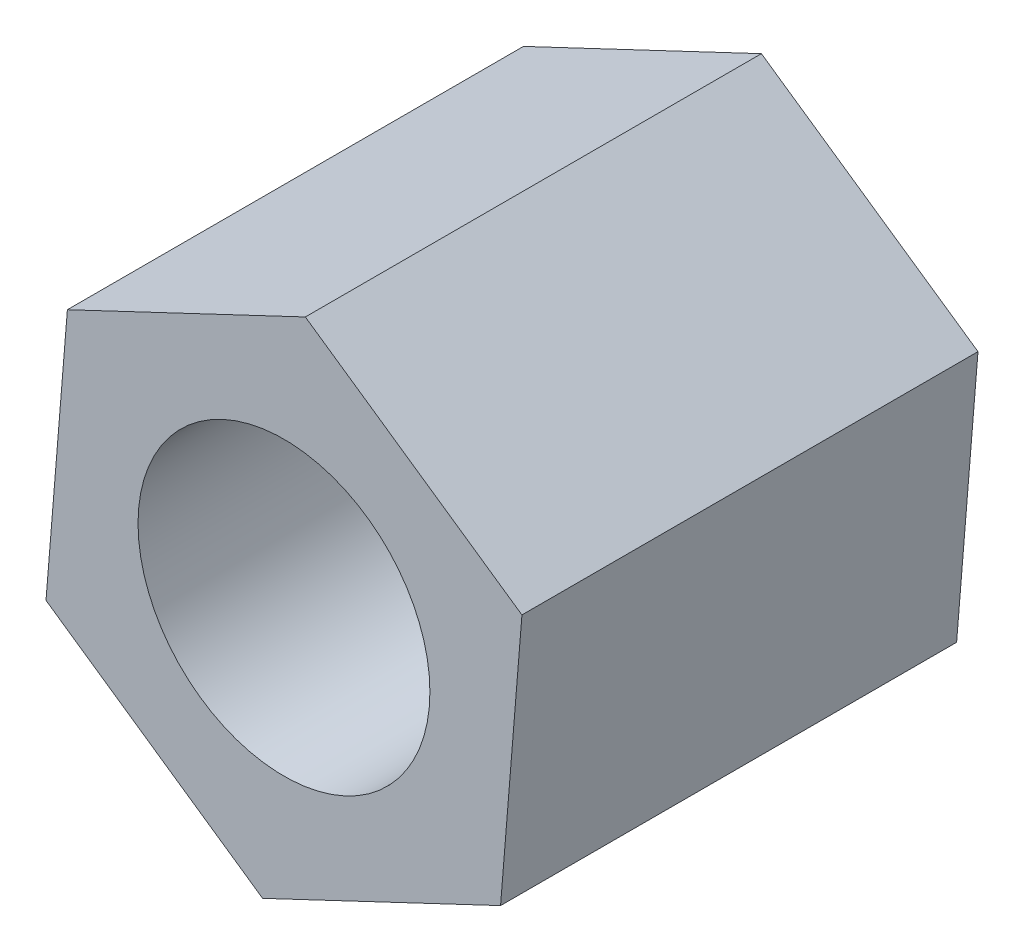
SolidWorks part; units mm, degrees
ref_plane "Front Plane" through (0, 0, 0) normal (0, 0, 1) x (1, 0, 0)
ref_plane "Top Plane" through (0, 0, 0) normal (0, 1, 0) x (1, 0, 0)
ref_plane "Right Plane" through (0, 0, 0) normal (1, 0, 0) x (0, 0, -1)
sketch "Sketch1" plane through (0, 0, 0) normal (0, 0, 1) x (1, 0, 0)
  line L1 (-2.3745, 1.6416) -> (-2.609, -1.2356)
  line L2 (-2.609, -1.2356) -> (-0.2344, -2.8772)
  line L3 (-0.2344, -2.8772) -> (2.3745, -1.6416)
  line L4 (2.3745, -1.6416) -> (2.609, 1.2356)
  line L5 (2.609, 1.2356) -> (0.2344, 2.8772)
  line L6 (0.2344, 2.8772) -> (-2.3745, 1.6416)
  circle A0 centre (0, 0) radius 2.5 construction
  dimension "D1" = 5
extrude "Boss-Extrude1" add sketch "Sketch1" along normal blind 5
sketch "Sketch2" plane through (0, 0, 5) normal (0, 0, 1) x (1, 0, 0)
  circle A0 centre (0, 0) radius 1.6
extrude "Cut-Extrude1" cut sketch "Sketch2" against normal blind 5
